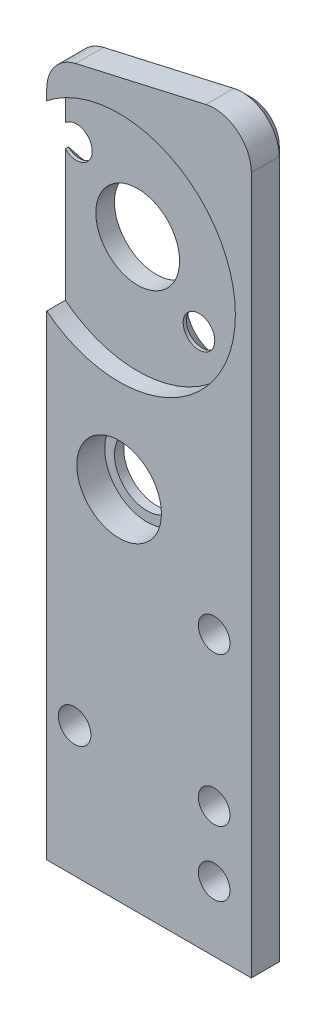
SolidWorks part; units mm, degrees
ref_plane "Plano frontal" through (0, 0, 0) normal (0, 0, 1) x (1, 0, 0)
ref_plane "Plano superior" through (0, 0, 0) normal (0, 1, 0) x (1, 0, 0)
ref_plane "Plano direito" through (0, 0, 0) normal (1, 0, 0) x (0, 0, -1)
sketch "Esboço1" plane through (0, 0, 0) normal (0, 0, 1) x (1, 0, 0)
  line L0 (0, 0) -> (22, 0)
  line L1 (22, 0) -> (22, 80)
  line L2 (22, 80) -> (0, 75)
  line L3 (0, 75) -> (0, 0)
  dimension "D1" = 22
  dimension "D2" = 80
  dimension "D3" = 75
extrude "Ressalto-extrusão1" add sketch "Esboço1" along normal blind 4
fillet "Filete1" radius 4 2 edges at (22, 80, 2) (0, 75, 2)
chamfer "Chanfro1" distance 1 angle 45 5 edges at (0, 35.9035, 0) (0.8738, 74.3025, 0) (10.1135, 77.2985, 0) (20.4954, 78.1151, 0) (22, 37.4945, 0)
sketch "Esboço2" plane through (0, 0, 4) normal (0, 0, 1) x (1, 0, 0)
  line L0 (0, 71.8071) -> (0, 0) construction
  point P0 (14.1, 34.4)
  dimension "D1" = 34.4
  dimension "D2" = 14.1
sketch "Esboço4" plane through (0, 0, 0) normal (0, 0, -1) x (-1, 0, 0)
  line L0 (0, 0) -> (-7.7809, 0) construction
  line L1 (-1, 0) -> (-21, 0) construction
  line L2 (-7.7809, 0) -> (-7.7809, 38.3937) construction
  line L3 (0, 0) -> (10, 0) construction
  line L4 (10, 0) -> (10, 13) construction
  line L5 (10, 13) -> (-21, 13) construction
  line L6 (10, 13) -> (-7.7809, 38.3937) construction
  circle A0 centre (10, 13) radius 31 construction
  dimension "D3" = 62
  dimension "D1" = 10
  dimension "D2" = 13
  dimension "D4" = 55
hole_wizard "Furo de diâmetro Ø7.0 (7)1" positions "3DSketch1" profile "Esboço5" hole size "Ø7.0" standard "ISO" end condition through all
sketch3d "3DSketch1"
  point P0 (7.7809, 38.3937, 0)
sketch "Esboço5" plane through (7.7809, 38.3937, 0) normal (1, 0, 0) x (0, 1, 0)
  line L0 (0, 0) -> (0, 4)
  line L1 (0, 4) -> (3.5, 4)
  line L2 (3.5, 4) -> (3.5, 0)
  line L5 (3.5, 0) -> (0, 0)
  line L11 (0, -6.35) -> (0, 107.95) construction
  dimension "Thru Hole Dia." = 7
  dimension "Thru Hole Depth" = 4
sketch "Esboço7" plane through (0, 0, 0) normal (0, 0, -1) x (-1, 0, 0)
  line L0 (-18, 7) -> (-18, 14) construction
  line L1 (-1, 0) -> (-21, 0) construction
  line L2 (-18, 14) -> (-3, 14) construction
  line L3 (0, 71.8071) -> (0, 0) construction
  point P0 (-18, 7)
  dimension "D1" = 18
  dimension "D2" = 7
  dimension "D3" = 7
  dimension "D4" = 3
hole_wizard "Escareado para parafuso com cabeça escareada elevada de M31" positions "3DSketch3" profile "Esboço8" countersink size "M3" standard "ISO" end condition through all
sketch3d "3DSketch3"
  point P0 (18, 7, 0)
  point P3 (18, 14, 0)
sketch "Esboço8" plane through (18, 7, 0) normal (1, 0, 0) x (0, 1, 0)
  line L0 (0, 0) -> (0, 4)
  line L1 (0, 4) -> (1.7, 4)
  line L2 (1.7, 4) -> (1.7, 1.45)
  line L3 (1.7, 1.45) -> (3.15, 0)
  line L5 (3.15, 0) -> (0, 0)
  line L6 (-1.7, 1.45) -> (-3.15, 0) construction
  line L11 (0, -6.35) -> (0, 107.95) construction
  dimension "Thru Hole Dia." = 3.4
  dimension "Thru Hole Depth" = 4
  dimension "Near C'Sink Dia." = 6.3
  dimension "Near C'Sink Angle" = 90
sketch "Esboço9" plane through (0, 0, 0) normal (0, -1, 0) x (1, 0, 0)
  line L0 (0, 4) -> (0, 0) construction
  line L1 (0, 2) -> (22, 2) construction
  line L2 (22, 4) -> (22, 1) construction
  point P8 (4, 2)
  point P9 (8, 2)
  point P10 (12, 2)
  dimension "D1" = 4
  dimension "D2" = 4
  dimension "D3" = 4
hole_wizard "Broca de rosquear para tarraxa de M21" positions "3DSketch4" profile "Esboço11" hole size "M2" standard "ISO"
sketch3d "3DSketch4"
  point P0 (4, 0, 2)
  point P6 (12, 0, 2)
sketch "Esboço11" plane through (4, 0, 2) normal (1, 0, 0) x (0, 0, -1)
  line L0 (0, 0) -> (0, 8.4807)
  line L1 (0, 8.4807) -> (0.8, 8)
  line L2 (0.8, 8) -> (0.8, 0)
  line L5 (0.8, 0) -> (0, 0)
  line L10 (0, 8.4807) -> (-0.8, 8) construction
  line L11 (0, -6.35) -> (0, 107.95) construction
  dimension "Hole Dia." = 1.6
  dimension "Hole Depth" = 8
  dimension "Drill Angle" = 118
sketch "Esboço12" plane through (0, 0, 4) normal (0, 0, 1) x (1, 0, 0)
  circle A0 centre (7.7809, 38.3937) radius 3.5 construction
  circle A1 centre (7.7809, 38.3937) radius 4.55
  point P0 (7.7809, 38.3937)
  dimension "D1" = 9.1
sketch "Esboço15" plane through (0, 0, 0) normal (0, 0, -1) x (-1, 0, 0)
  line L0 (-7.7809, 38.3937) -> (-7.7809, 49.8937) construction
  line L1 (-7.7809, 49.8937) -> (-7.7809, 60.8937) construction
  line L4 (-14.3689, 55.3657) -> (-1.1929, 66.4217) construction
  line L6 (0, 71.8071) -> (0, 0) construction
  circle A0 centre (-7.7809, 49.8937) radius 11.5 construction
  circle A1 centre (-7.7809, 60.8937) radius 8.6 construction
  circle A2 centre (-7.7809, 49.8937) radius 4.6
  point P4 (-7.7809, 49.8937)
  dimension "D2" = 17.2
  dimension "D6" = 9.2
  dimension "D1" = 11.5
  dimension "D3" = 50
  dimension "D4" = 180
  dimension "D5" = 0
  dimension "D7" = 11
hole_wizard "Furo de diâmetro Ø9.0 (9)3" positions "3DSketch9" profile "Esboço22" hole size "Ø9.0" standard "ISO" end condition through all
sketch3d "3DSketch9"
  point P12 (7.7809, 60.8937, 0)
sketch "Esboço22" plane through (7.7809, 60.8937, 0) normal (1, 0, 0) x (0, 1, 0)
  line L0 (0, 0) -> (0, 4)
  line L1 (0, 4) -> (4.5, 4)
  line L2 (4.5, 4) -> (4.5, 0)
  line L5 (4.5, 0) -> (0, 0)
  line L11 (0, -6.35) -> (0, 107.95) construction
  dimension "Thru Hole Dia." = 9
  dimension "Thru Hole Depth" = 4
sketch "Esboço24" plane through (0, 0, 4) normal (0, 0, 1) x (1, 0, 0)
  circle A0 centre (7.7809, 49.8937) radius 4.6
  circle A1 centre (7.7809, 49.8937) radius 4.6 construction
  point P0 (7.7809, 49.8937)
hole_wizard "Escareado para parafuso Allen sextavado escareado de M31" positions "3DSketch14" profile "Esboço28" countersink size "M3" standard "ISO" end condition through all
sketch3d "3DSketch14"
  point P0 (14.3689, 55.3657, 0)
  point P3 (1.1929, 66.4217, 0)
sketch "Esboço28" plane through (14.3689, 55.3657, 0) normal (1, 0, 0) x (0, 1, 0)
  line L0 (0, 0) -> (0, 4)
  line L1 (0, 4) -> (1.7, 4)
  line L2 (1.7, 4) -> (1.7, 1.66)
  line L3 (1.7, 1.66) -> (3.36, 0)
  line L5 (3.36, 0) -> (0, 0)
  line L6 (-1.7, 1.66) -> (-3.36, 0) construction
  line L11 (0, -6.35) -> (0, 107.95) construction
  dimension "Thru Hole Dia." = 3.4
  dimension "Thru Hole Depth" = 4
  dimension "Near C'Sink Dia." = 6.72
  dimension "Near C'Sink Angle" = 90
sketch "Esboço30" plane through (0, 0, 0) normal (0, 0, -1) x (-1, 0, 0)
  line L0 (-22, 0) -> (-22, 74.9889) construction
  line L1 (0, 0) -> (-22, 0) construction
  point P0 (-18, 30)
  dimension "D1" = 4
  dimension "D2" = 30
hole_wizard "Escareado para parafuso com cabeça escareada chata de M31" positions "3DSketch16" profile "Esboço31" countersink size "M3" standard "ISO"
sketch3d "3DSketch16"
  point P0 (18, 30, 0)
sketch "Esboço31" plane through (18, 30, 0) normal (1, 0, 0) x (0, 1, 0)
  line L0 (0, 0) -> (0, 5.0215)
  line L1 (0, 5.0215) -> (1.7, 4)
  line L2 (1.7, 4) -> (1.7, 1.45)
  line L3 (1.7, 1.45) -> (3.15, 0)
  line L5 (3.15, 0) -> (0, 0)
  line L6 (-1.7, 1.45) -> (-3.15, 0) construction
  line L10 (0, 5.0215) -> (-1.7, 4) construction
  line L11 (0, -6.35) -> (0, 107.95) construction
  dimension "Hole Dia." = 3.4
  dimension "Hole Depth" = 4
  dimension "Near C'Sink Dia." = 6.3
  dimension "Near C'Sink Angle" = 90
  dimension "Drill Angle" = 118
extrude "Corte-extrusão1" cut sketch "Esboço12" against normal blind 3
sketch "Esboço32" plane through (0, 0, 4) normal (0, 0, 1) x (1, 0, 0)
  line L0 (7.7809, 68.8937) -> (7.7809, 49.8937) construction
  line L1 (0, 71.8071) -> (0, 67.6329) construction
  line L2 (7.7809, 68.8937) -> (7.7809, 26.8937) construction
  dimension "D1" = 19
  dimension "D2" = 42
hole_wizard "Furo de diâmetro Ø3.5 (3.5)1" positions "3DSketch19" profile "Esboço35" hole size "Ø3.5" standard "ISO" end condition through all
sketch3d "3DSketch19"
  point P0 (3, 14, 0)
sketch "Esboço35" plane through (3, 14, 0) normal (1, 0, 0) x (0, 1, 0)
  line L0 (0, 0) -> (0, 4)
  line L1 (0, 4) -> (1.75, 4)
  line L2 (1.75, 4) -> (1.75, 0)
  line L5 (1.75, 0) -> (0, 0)
  line L11 (0, -6.35) -> (0, 107.95) construction
  dimension "Thru Hole Dia." = 3.5
  dimension "Thru Hole Depth" = 4
sketch "Esboço36" plane through (0, 0, 4) normal (0, 0, 1) x (1, 0, 0)
  circle A0 centre (7.7809, 60.8937) radius 12.5
  dimension "D1" = 25
extrude "Corte-extrusão4" cut sketch "Esboço36" against normal blind 2
